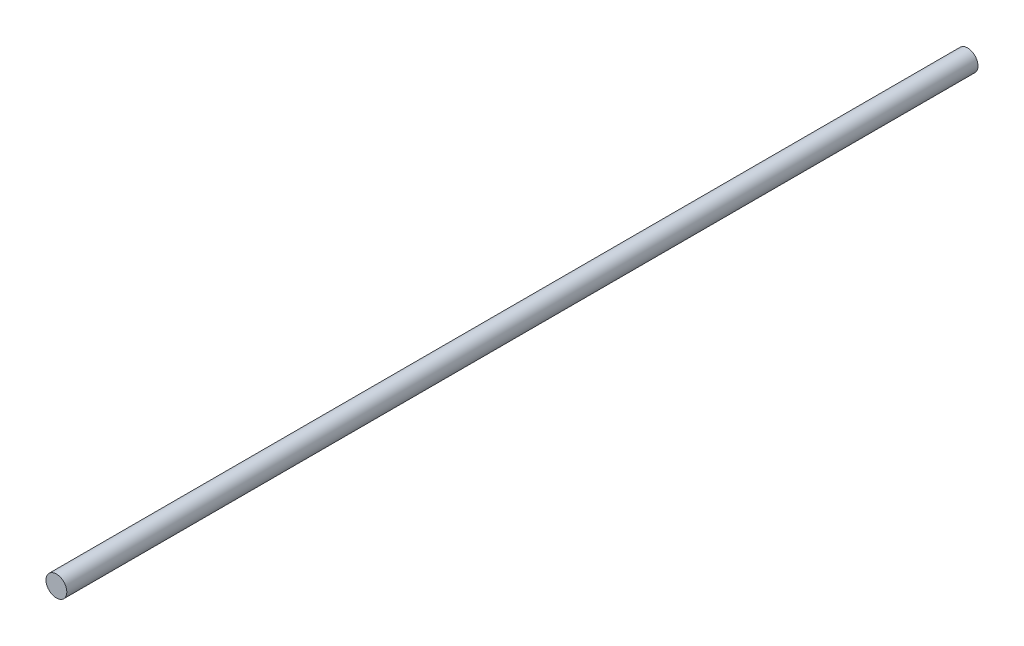
SolidWorks part; units mm, degrees
ref_plane "Front Plane" through (0, 0, 0) normal (0, 0, 1) x (1, 0, 0)
ref_plane "Top Plane" through (0, 0, 0) normal (0, 1, 0) x (1, 0, 0)
ref_plane "Right Plane" through (0, 0, 0) normal (1, 0, 0) x (0, 0, -1)
sketch "Sketch1" plane through (0, 0, 0) normal (0, 0, 1) x (1, 0, 0)
  circle A0 centre (0, 0) radius 6
extrude "Boss-Extrude1" add sketch "Sketch1" along normal blind 525
sketch "Sketch3" plane through (0, 0, 525) normal (0, 0, 1) x (1, 0, 0)
  circle A0 centre (0, 0) radius 5.25
sketch3d "3DSketch1"
  line L0 (0, 6.0062, 599.8503) -> (0, 6.0062, 599.3913)
  line L1 (0, 6.0062, 599.8503) -> (0, 6.0062, 600.3093)
  line L3 (0, 6.0062, 600.3093) -> (0, 4.9862, 599.8503)
  line L4 (0, 6.0062, 599.3913) -> (0, 4.9862, 599.8503)
